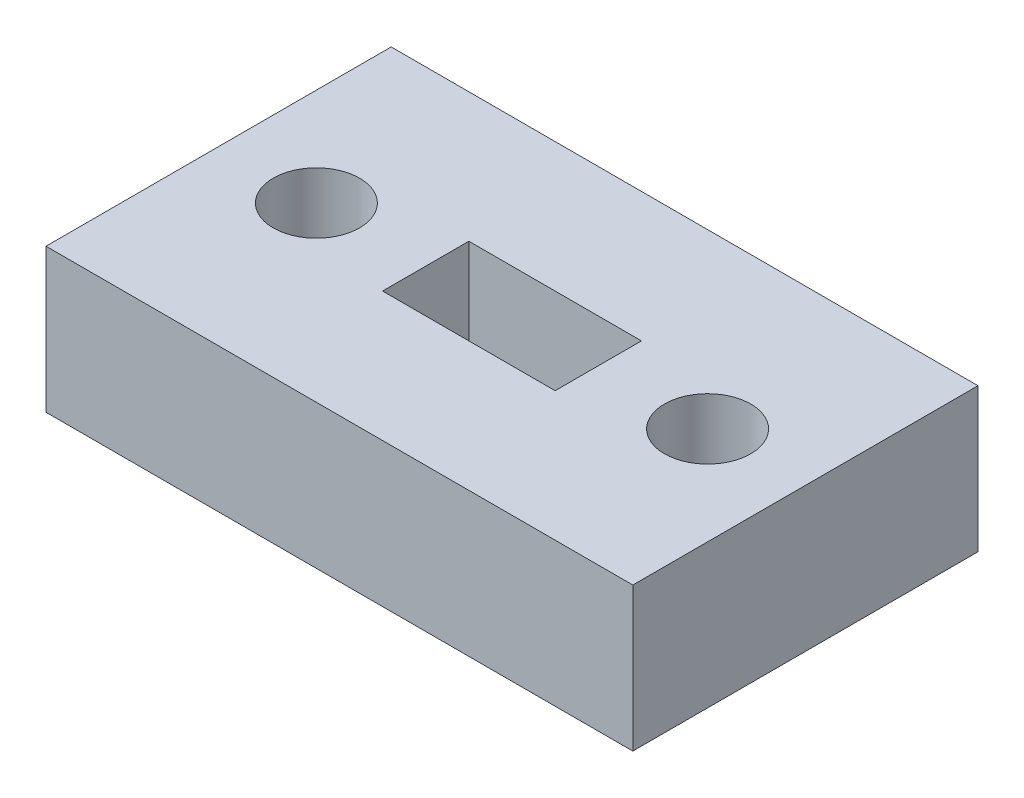
SolidWorks part; units mm, degrees
material "6061 Alloy"
ref_plane "Front Plane" through (0, 0, 0) normal (0, 0, 1) x (1, 0, 0)
ref_plane "Top Plane" through (0, 0, 0) normal (0, 1, 0) x (1, 0, 0)
ref_plane "Right Plane" through (0, 0, 0) normal (1, 0, 0) x (0, 0, -1)
sketch "Sketch1" plane through (0, 0, 0) normal (0, 1, 0) x (1, 0, 0)
  line L1 (0, 0) -> (25.908, 0)
  line L2 (0, 0) -> (0, 15.24)
  line L3 (0, 15.24) -> (25.908, 15.24)
  line L4 (25.908, 0) -> (25.908, 15.24)
  line L5 (9.144, 5.715) -> (16.764, 5.715)
  line L6 (9.144, 5.715) -> (9.144, 9.525)
  line L7 (9.144, 9.525) -> (16.764, 9.525)
  line L8 (16.764, 5.715) -> (16.764, 9.525)
  circle A0 centre (4.318, 7.62) radius 1.905
  circle A1 centre (21.59, 7.62) radius 1.905
  dimension "D3" = 4.318
  dimension "D4" = 7.62
  dimension "D5" = 4.318
  dimension "D6" = 3.81
  dimension "D7" = 3.81
  dimension "D1" = 25.908
  dimension "D2" = 15.24
  dimension "D8" = 7.62
  dimension "D9" = 3.81
  dimension "D10" = 5.715
  dimension "D11" = 9.144
extrude "Boss-Extrude1" add sketch "Sketch1" along normal blind 6.35
